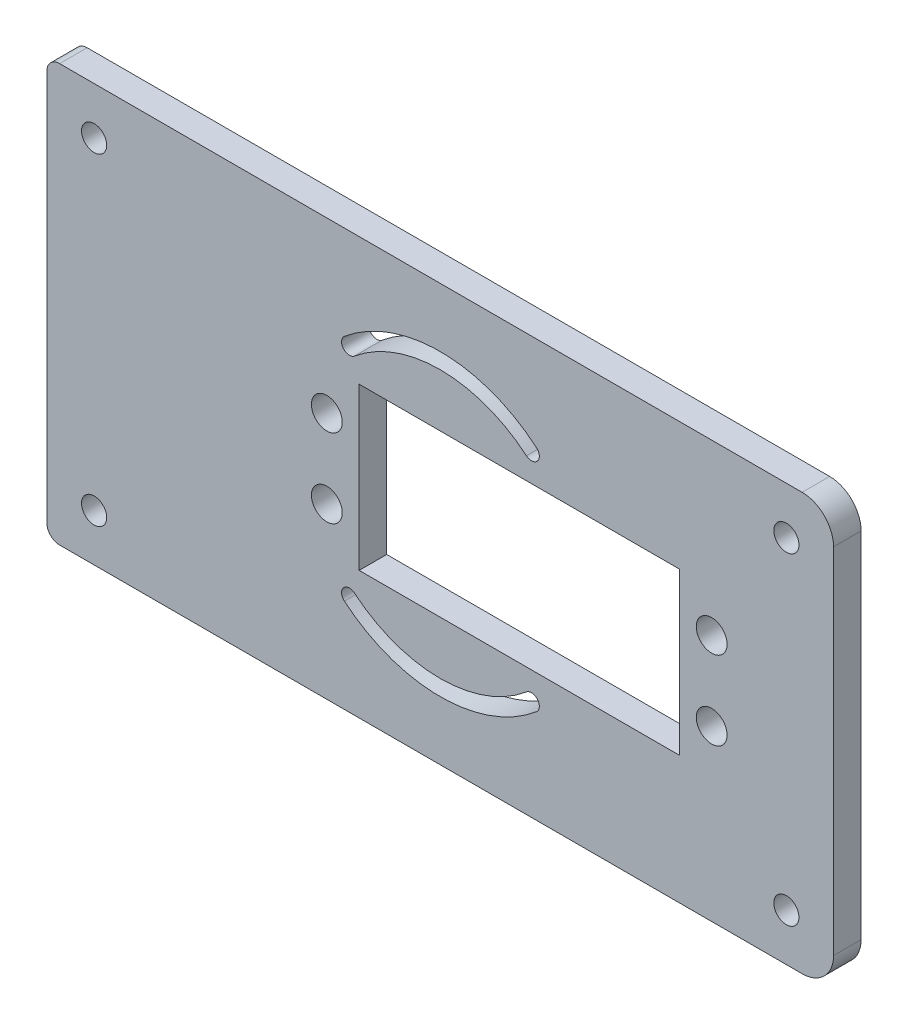
SolidWorks part; units mm, degrees
material "Balsa"
ref_plane "Front Plane" through (0, 0, 0) normal (0, 0, 1) x (1, 0, 0)
ref_plane "Top Plane" through (0, 0, 0) normal (0, 1, 0) x (1, 0, 0)
ref_plane "Right Plane" through (0, 0, 0) normal (1, 0, 0) x (0, 0, -1)
sketch "Sketch1" plane through (0, 0, 0) normal (0, 0, 1) x (1, 0, 0)
  line L5 (-0.0442, 0) -> (-0.0442, 26.5) construction
  line L6 (-48.429, -26.5) -> (48.3406, -26.5)
  line L34 (-50.0442, -24.8848) -> (-50.0442, 24.8848)
  line L37 (-48.429, 26.5) -> (48.3406, 26.5)
  line L41 (48.3406, 26.5) -> (45.9558, 26.5)
  line L42 (49.9558, 22.5) -> (49.9558, -22.5)
  line L47 (-0.0442, 0) -> (-0.0442, -26.5) construction
  line L48 (-0.0442, 0) -> (-50.0442, 0) construction
  line L49 (-0.0442, 0) -> (49.9558, 0) construction
  line L50 (-22.2361, -26.5) -> (22.2361, 26.5) construction
  line L51 (-22.2361, 26.5) -> (22.2361, -26.5) construction
  line L52 (45.9558, -26.5) -> (48.3406, -26.5)
  line L54 (-14.4621, 9.5) -> (-14.4621, -9.5) construction
  line L61 (-10, 9.5) -> (-16.5, 9.5) construction
  line L62 (-10, -9.5) -> (-16.5, -9.5) construction
  line L63 (-10.3491, 10.2491) -> (30.3491, 10.2491)
  line L64 (-10.3491, 10.2491) -> (-10.3491, -10.2491)
  line L65 (-10.3491, -10.2491) -> (30.3491, -10.2491)
  line L66 (30.3491, 10.2491) -> (30.3491, -10.2491)
  circle A7 centre (43.9558, -20.5) radius 1.6
  circle A8 centre (43.9558, 20.5) radius 1.6
  circle A9 centre (-44.0442, 20.5) radius 1.6
  circle A10 centre (-44.0442, -20.5) radius 1.6
  arc A15 (-48.429, -26.5) -> (-50.0442, -24.8848) centre (-48.429, -24.8848) cw
  arc A16 (-48.429, 26.5) -> (-50.0442, 24.8848) centre (-48.429, 24.8848) ccw
  arc A17 (-11.5884, -13.8105) -> (11.5519, -13.767) centre (-0.0442, 0) ccw construction
  arc A18 (-12.2298, -14.5778) -> (12.1961, -14.5318) centre (-0.0442, 0) ccw
  arc A19 (-10.9471, -13.0433) -> (10.9077, -13.0022) centre (-0.0442, 0) ccw
  arc A20 (-10.9471, -13.0433) -> (-12.2298, -14.5778) centre (-11.5884, -13.8105) ccw
  arc A21 (12.1961, -14.5318) -> (10.9077, -13.0022) centre (11.5519, -13.767) ccw
  arc A22 (-11.5884, 13.8105) -> (11.5519, 13.767) centre (-0.0442, 0) cw construction
  arc A23 (-12.2298, 14.5778) -> (12.1961, 14.5318) centre (-0.0442, 0) cw
  arc A24 (-10.9471, 13.0433) -> (10.9077, 13.0022) centre (-0.0442, 0) cw
  arc A25 (-10.9471, 13.0433) -> (-12.2298, 14.5778) centre (-11.5884, 13.8105) cw
  arc A26 (12.1961, 14.5318) -> (10.9077, 13.0022) centre (11.5519, 13.767) cw
  arc A28 (45.9558, 26.5) -> (49.9558, 22.5) centre (45.9558, 22.5) cw
  arc A29 (49.9558, -22.5) -> (45.9558, -26.5) centre (45.9558, -22.5) cw
  circle A37 centre (-14.4621, 5) radius 1.9613
  circle A38 centre (0, 0) radius 4.8808
  circle A39 centre (-14.4621, -5) radius 1.9613
  circle A40 centre (34.4621, -5) radius 1.9613
  circle A41 centre (34.4621, 5) radius 1.9613
  point P0 (0, 0)
  point P4 (-0.0103, -18)
  point P47 (-0.0103, 18)
  dimension "D6" = 6
  dimension "D11" = 4.113
  dimension "D1" = 3.2
  dimension "D14" = 40.6982
  dimension "D24" = 18
  dimension "D10" = 4
  dimension "D13" = 20.4982
  dimension "D2" = 6
  dimension "D3" = 6
  dimension "D4" = 6
  dimension "D5" = 6
  dimension "D7" = 6
  dimension "D8" = 6
  dimension "D9" = 6
  dimension "D12" = 5
  dimension "D15" = 100
  dimension "D19" = 50
  dimension "D21" = 50
  dimension "D23" = 53
  dimension "D25" = 2
extrude "Boss-Extrude1" add sketch "Sketch1" along normal blind 3.5
